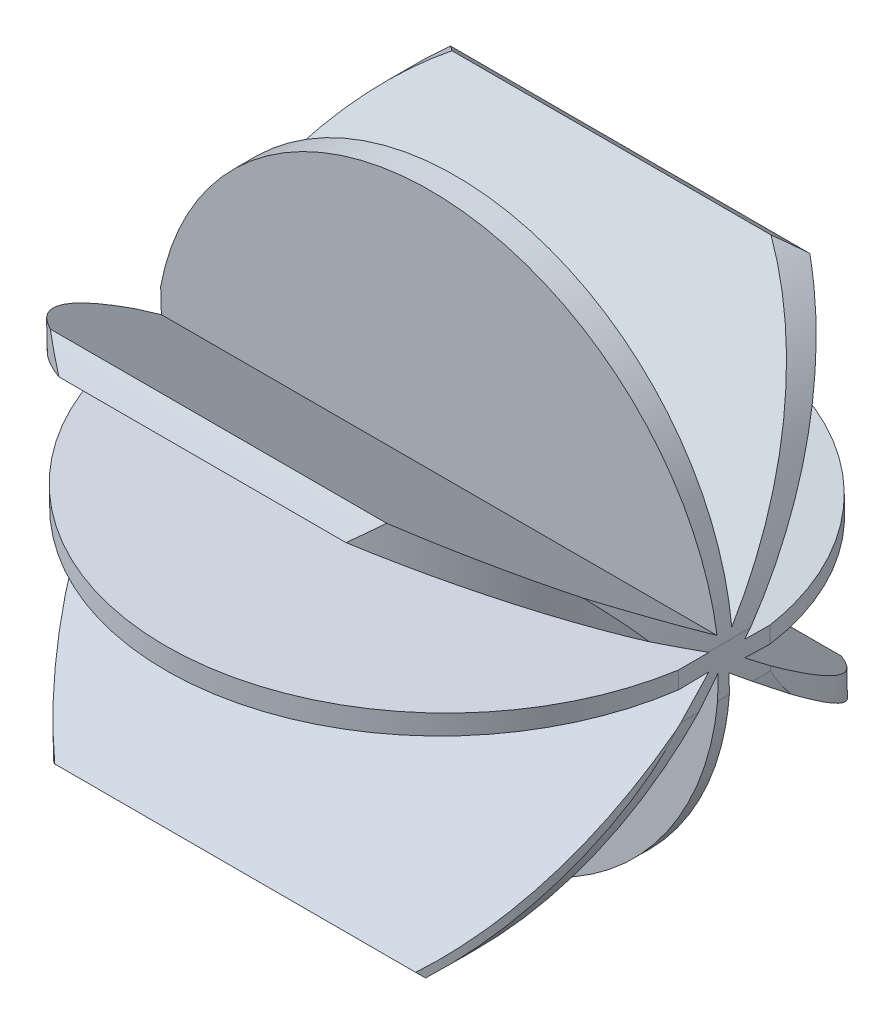
SolidWorks part; units mm, degrees
ref_plane "Front Plane" through (0, 0, 0) normal (0, 0, 1) x (1, 0, 0)
ref_plane "Top Plane" through (0, 0, 0) normal (0, 1, 0) x (1, 0, 0)
ref_plane "Right Plane" through (0, 0, 0) normal (1, 0, 0) x (0, 0, -1)
sketch "Sketch1" plane through (0, 0, 0) normal (1, 0, 0) x (0, 0, -1)
  circle A0 centre (-1.6129, 0) radius 58.4992
extrude "Boss-Extrude1" add sketch "Sketch1" along normal blind 95
sketch "Sketch2" plane through (0, 0, 0) normal (-1, 0, 0) x (0, 0, 1)
  line L0 (-34.6166, 50.0805) -> (-34.6166, 62.8956)
  line L1 (0, 3.5837) -> (-34.2937, 46.4288)
  line L3 (-37.4682, 43.5295) -> (-2.0463, 0.8177)
  line L4 (-2.0463, 0.8177) -> (-56.8862, 0)
  line L6 (-56.7735, -3.6294) -> (-2.0463, -1.93)
  line L7 (-2.0463, -1.93) -> (-45.251, -35.0131)
  line L9 (-42.7832, -38.0937) -> (0.6009, -2.8363)
  line L10 (0.6009, -2.8363) -> (0, -58.4769)
  line L12 (3.2259, -58.4769) -> (2.5058, -1.93)
  line L13 (2.5058, -1.93) -> (37.6766, -46.0605)
  line L15 (42.3527, -41.9813) -> (4.0466, -0.932)
  line L16 (4.0466, -0.932) -> (60.0803, -1.93)
  line L18 (60.0803, 1.93) -> (4.0466, 1.93)
  line L19 (4.0466, 1.93) -> (51.078, 31.2309)
  line L21 (48.2486, 35.3166) -> (2.5058, 3.5837)
  line L22 (2.5058, 3.5837) -> (4.0466, 58.4485)
  line L24 (-0.8207, 58.4485) -> (0, 3.5837)
  spline S0 degree 1 poles (-34.2937, 46.4288) (-34.6166, 50.0805) knots 0 0 1 1
  spline S1 degree 2 poles (4.0466, 58.4485) (39.2461, 77.7414) (48.2486, 35.3166) knots 0 0 0 1 1 1
  spline S2 degree 2 poles (51.078, 31.2309) (102.1468, 32.0288) (60.0803, 1.93) knots 0 0 0 1 1 1
  spline S3 degree 2 poles (60.0803, -1.93) (94.0499, -36.727) (42.3527, -41.9813) knots 0 0 0 1 1 1
  spline S4 degree 2 poles (37.6766, -46.0605) (44.9676, -79.6134) (3.2259, -58.4769) knots 0 0 0 1 1 1
  spline S5 degree 2 poles (-37.4682, 43.5295) (-81.7262, 46.4723) (-56.8862, 0) knots 0 0 0 1 1 1
  spline S6 degree 2 poles (-56.7735, -3.6294) (-82.6378, -33.7625) (-45.251, -35.0131) knots 0 0 0 1 1 1
  spline S7 degree 2 poles (-42.7832, -38.0937) (-42.1579, -81.2454) (0, -58.4769) knots 0 0 0 1 1 1
  spline S8 degree 1 poles (-34.6166, 62.8956) (-0.8207, 58.4485) knots 0 0 1 1
extrude "Cut-Extrude3" cut sketch "Sketch2" against normal blind 100
sketch "Sketch4" plane through (0, 0, 0) normal (-1, 0, 0) x (0, 0, 1)
  line L1 (-1.8523, 60.3541) -> (7.5208, 60.3541)
  line L2 (-1.8523, 60.3541) -> (-1.8523, 58.2672)
  line L3 (-1.8523, 58.2672) -> (7.5208, 58.2672)
  line L4 (7.5208, 60.3541) -> (7.5208, 58.2672)
  line L5 (-56.5528, -8.0129) -> (-59.0291, -8.0129)
  line L6 (-56.5528, -8.0129) -> (-56.5528, 4.5205)
  line L7 (-56.5528, 4.5205) -> (-59.0291, 4.5205)
  line L8 (-59.0291, -8.0129) -> (-59.0291, 4.5205)
extrude "Cut-Extrude4" cut sketch "Sketch4" against normal through all
sketch "Sketch5" plane through (0, 0, -56.5528) normal (0, 0, -1) x (-1, 0, 0)
  circle A0 centre (-47.0783, -2.0126) radius 48.0916
  circle A1 centre (-47.0783, -2.0126) radius 85.1859
extrude "Cut-Extrude6" cut sketch "Sketch5" against normal through all
sketch "Sketch6" plane through (0, -0.8596, -0.0153) normal (0, -0.9998, -0.0178) x (-1, 0, 0)
  circle A0 centre (-47.6738, -1.4548) radius 47.9656
  circle A1 centre (-47.6738, -1.4548) radius 79.1793
extrude "Cut-Extrude9" cut sketch "Sketch6" along normal through all both and the other way through all
sketch "Sketch7" plane through (95, 0, 0) normal (1, 0, 0) x (0, 0, -1)
  circle A0 centre (-2.5058, -1.93) radius 49.5015
  circle A1 centre (-2.5058, -1.93) radius 65.6702
extrude "Cut-Extrude11" cut sketch "Sketch7" against normal blind 100
